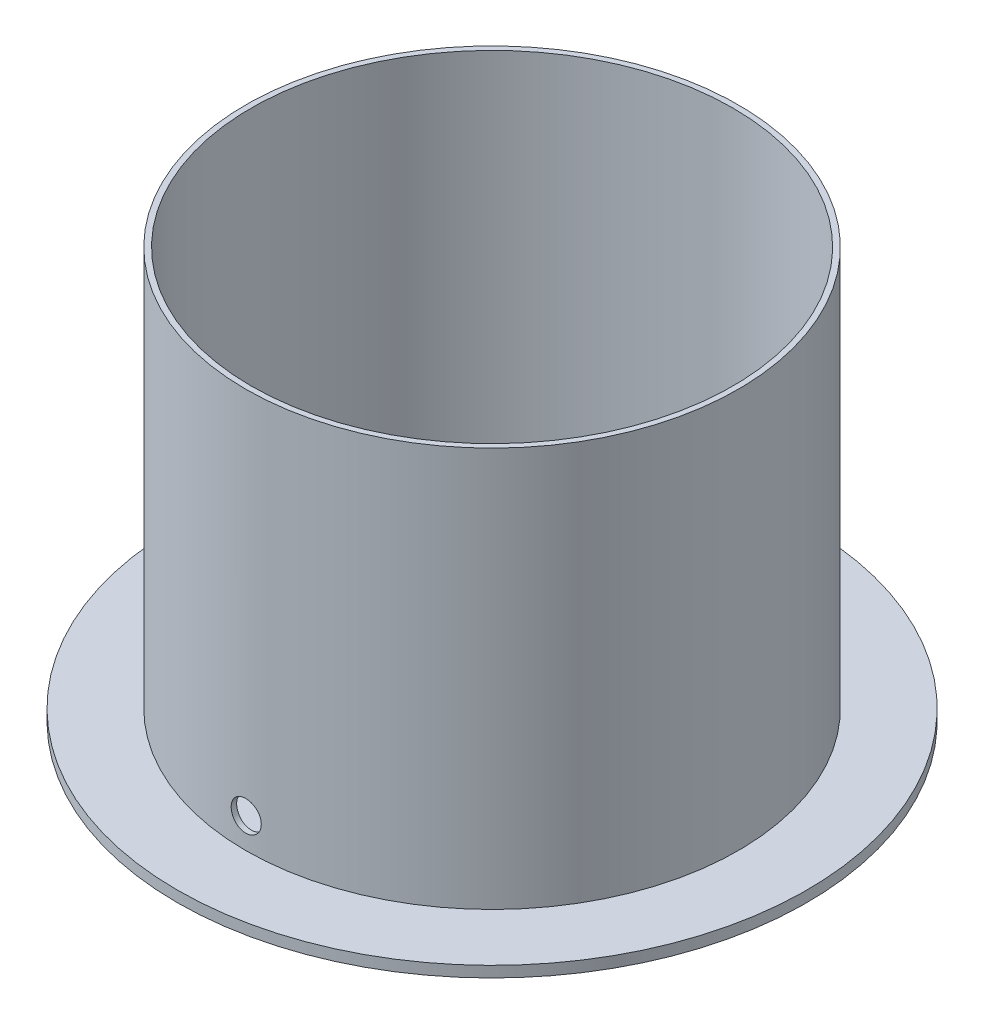
SolidWorks part; units mm, degrees
material "PE High Density"
ref_plane "Front Plane" through (0, 0, 0) normal (0, 0, 1) x (1, 0, 0)
ref_plane "Top Plane" through (0, 0, 0) normal (0, 1, 0) x (1, 0, 0)
ref_plane "Right Plane" through (0, 0, 0) normal (1, 0, 0) x (0, 0, -1)
sketch "Base Flange Sketch" plane through (0, 0, 0) normal (0, 1, 0) x (1, 0, 0)
  circle A0 centre (0, 0) radius 230
  dimension "D1" = 460
extrude "Base Flange" add sketch "Base Flange Sketch" along normal blind 8
sketch "Tank Wall Sketch" plane through (0, 0, 0) normal (0, 1, 0) x (1, 0, 0)
  circle A0 centre (0, 0) radius 180
  circle A1 centre (0, 0) radius 176
  dimension "D1" = 360
  dimension "D2" = 352
extrude "Tank Wall" add sketch "Tank Wall Sketch" along normal blind 300
sketch "Port Holes Sketch" plane through (0, 0, 0) normal (0, 0, 1) x (1, 0, 0)
  circle A0 centre (0, 30) radius 11
  dimension "D2" = 22
  dimension "D1" = 30
extrude "Tap + Drain Ports" cut sketch "Port Holes Sketch" against normal through all and the other way through all
